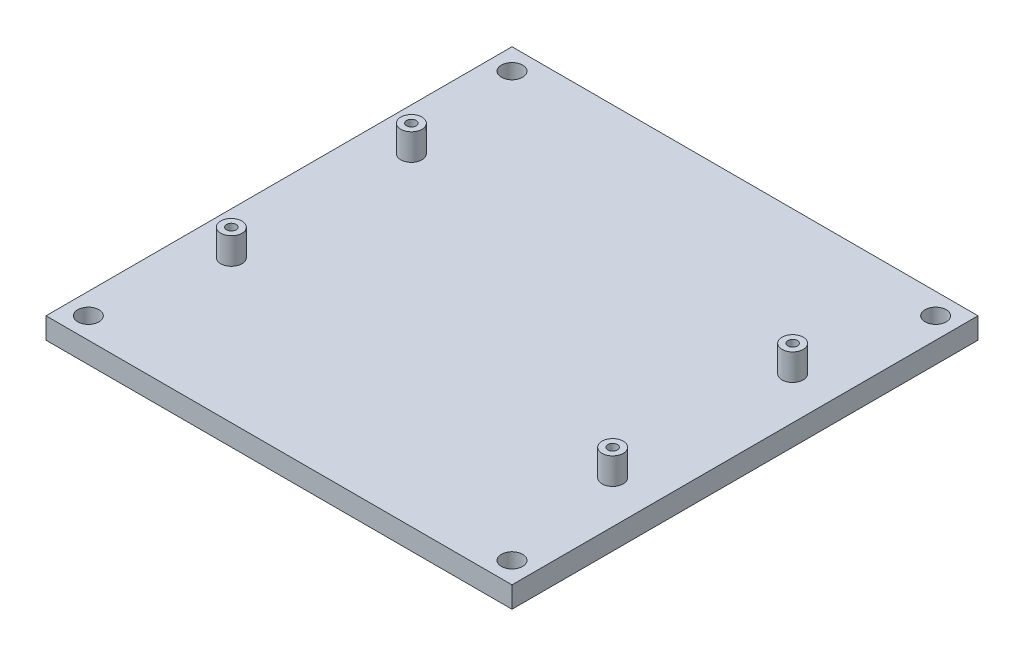
SolidWorks part; units mm, degrees
ref_plane "Front Plane" through (0, 0, 0) normal (0, 0, 1) x (1, 0, 0)
ref_plane "Top Plane" through (0, 0, 0) normal (0, 1, 0) x (1, 0, 0)
ref_plane "Right Plane" through (0, 0, 0) normal (1, 0, 0) x (0, 0, -1)
sketch "Sketch1" plane through (0, 0, 0) normal (0, 1, 0) x (1, 0, 0)
  line L0 (69.85, -69.85) -> (-69.85, -69.85)
  line L1 (69.85, -69.85) -> (69.85, 69.85)
  line L2 (69.85, 69.85) -> (-69.85, 69.85)
  line L3 (-69.85, -69.85) -> (-69.85, 69.85)
  dimension "D1" = 139.7
  dimension "D2" = 69.85
  dimension "D3" = 69.85
extrude "Boss-Extrude1" add sketch "Sketch1" along normal blind 6.35
sketch "Sketch2" plane through (0, 6.35, 0) normal (0, 1, 0) x (1, 0, 0)
  line L0 (-69.85, -69.85) -> (69.85, -69.85) construction
  line L1 (-69.85, 69.85) -> (-69.85, -69.85) construction
  line L2 (0, -55) -> (0, 55) construction
  line L4 (-55, 0) -> (55, 0) construction
  line L5 (69.85, -69.85) -> (69.85, 69.85) construction
  circle A0 centre (-63.5, -63.5) radius 3.175
  circle A4 centre (63.5, -63.5) radius 3.175
  circle A5 centre (63.5, 63.5) radius 3.175
  circle A6 centre (-63.5, 63.5) radius 3.175
  dimension "D1" = 6.35
  dimension "D2" = 6.35
  dimension "D3" = 6.35
extrude "Cut-Extrude1" cut sketch "Sketch2" against normal blind 6.35
sketch "Sketch4" plane through (0, 6.35, 0) normal (0, 1, 0) x (1, 0, 0)
  circle A0 centre (-57.15, -26.9875) radius 1.4288
  circle A1 centre (57.15, -26.9875) radius 1.4288
  circle A2 centre (-57.15, 26.9875) radius 1.4288
  circle A3 centre (57.15, 26.9875) radius 1.4287
  circle A4 centre (-57.15, 26.9875) radius 3.175
  circle A5 centre (-57.15, -26.9875) radius 3.175
  circle A6 centre (57.15, -26.9875) radius 3.175
  circle A7 centre (57.15, 26.9875) radius 3.175
  point P13 (0, 0)
  point P14 (0, 0)
  point P16 (0, 0)
  dimension "D3" = 2.8575
  dimension "D4" = 2.8575
  dimension "D5" = 2.8575
  dimension "D6" = 2.8575
  dimension "D9" = 6.35
  dimension "D10" = 6.35
  dimension "D11" = 6.35
  dimension "D12" = 6.35
  dimension "D15" = 42.8625
  dimension "D1" = 114.3
  dimension "D2" = 53.975
  dimension "D7" = 114.3
  dimension "D8" = 53.975
  dimension "D13" = 12.7
  dimension "D14" = 42.8625
  dimension "D16" = 42.8625
extrude "Boss-Extrude2" add sketch "Sketch4" along normal blind 7.9375
